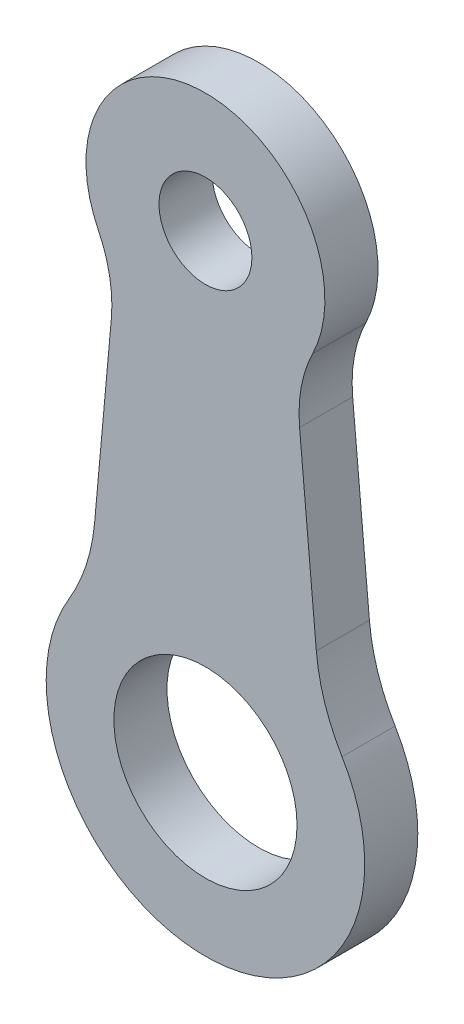
SolidWorks part; units mm, degrees
ref_plane "Front Plane" through (0, 0, 0) normal (0, 0, 1) x (1, 0, 0)
ref_plane "Top Plane" through (0, 0, 0) normal (0, 1, 0) x (1, 0, 0)
ref_plane "Right Plane" through (0, 0, 0) normal (1, 0, 0) x (0, 0, -1)
sketch "Sketch1" plane through (0, 0, 0) normal (0, 0, 1) x (1, 0, 0)
  line L2 (-4.5, 17.67) -> (-1.75, 17.67) construction
  line L3 (-1.75, 17.67) -> (1.75, 17.67) construction
  line L4 (1.75, 17.67) -> (4.5, 17.67) construction
  line L5 (-3.5454, 13.027) -> (-4.1766, 6.056)
  line L6 (6, 0) -> (3.45, 0) construction
  line L7 (3.45, 0) -> (-3.45, 0) construction
  line L8 (-3.45, 0) -> (-6, 0) construction
  line L9 (3.5454, 13.027) -> (4.1766, 6.056)
  line L10 (3.125, 17.67) -> (3.3927, 14.7137) construction
  line L11 (-3.125, 17.67) -> (-3.3927, 14.7137) construction
  line L12 (-4.725, 0) -> (-4.3509, 4.1316) construction
  line L13 (4.725, 0) -> (4.3509, 4.1316) construction
  line L14 (0, 17.67) -> (0, 0) construction
  circle A8 centre (0, 17.67) radius 1.75
  circle A9 centre (0, 0) radius 3.45
  arc A10 (-5.1453, 3.0864) -> (5.1453, 3.0864) centre (0, 0) ccw
  arc A11 (4.0382, 15.6843) -> (-4.0382, 15.6843) centre (0, 17.67) ccw
  arc A12 (3.5454, 13.027) -> (4.0382, 15.6843) centre (8.525, 13.4779) cw
  arc A13 (-3.5454, 13.027) -> (-4.0382, 15.6843) centre (-8.525, 13.4779) ccw
  arc A14 (4.1766, 6.056) -> (5.1453, 3.0864) centre (11.1481, 6.6873) ccw
  arc A15 (-4.1766, 6.056) -> (-5.1453, 3.0864) centre (-11.1481, 6.6873) cw
  dimension "D3" = 12
  dimension "D4" = 9
  dimension "D5" = 3.5
  dimension "D6" = 6.9
  dimension "D7" = 5
  dimension "D8" = 7
  dimension "D9" = 17.67
extrude "Boss-Extrude1" add sketch "Sketch1" along normal blind 2
